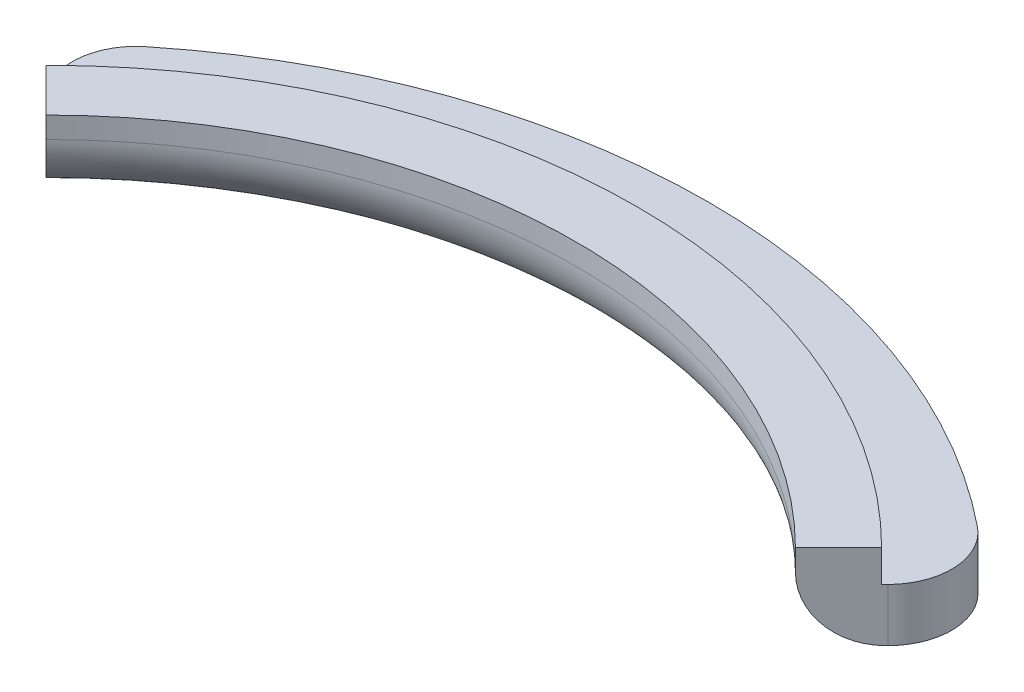
SolidWorks part; units mm, degrees
ref_plane "Front Plane" through (0, 0, 0) normal (0, 0, 1) x (1, 0, 0)
ref_plane "Top Plane" through (0, 0, 0) normal (0, 1, 0) x (1, 0, 0)
ref_plane "Right Plane" through (0, 0, 0) normal (1, 0, 0) x (0, 0, -1)
sketch "Sketch1" plane through (0, 0, 0) normal (0, 1, 0) x (1, 0, 0)
  line L0 (0, 0) -> (0, 15.875) construction
  line L1 (0, 0) -> (8.9803, 8.9803) construction
  line L2 (0, 0) -> (-8.9803, 8.9803) construction
  line L3 (-8.9803, 8.9803) -> (-11.2253, 11.2253)
  line L4 (8.9803, 8.9803) -> (11.2253, 11.2253)
  arc A0 (8.9803, 8.9803) -> (-8.9803, 8.9803) centre (0, 0) ccw
  arc A1 (11.2253, 11.2253) -> (-11.2253, 11.2253) centre (0, 0) ccw
  dimension "D1" = 31.75
  dimension "D2" = 25.4
  dimension "D3" = 45
  dimension "D4" = 45
extrude "Boss-Extrude1" add sketch "Sketch1" along normal blind 2.032
sketch "Sketch2" plane through (0, 2.032, 0) normal (0, 1, 0) x (1, 0, 0)
  line L0 (-11.2253, 11.2253) -> (-8.9803, 8.9803) construction
  line L1 (8.9803, 8.9803) -> (11.2253, 11.2253) construction
  line L2 (10.013, 10.013) -> (11.2253, 11.2253)
  line L3 (-11.2253, 11.2253) -> (-10.013, 10.013)
  arc A0 (-10.013, 10.013) -> (10.013, 10.013) centre (0, 0) cw
  arc A1 (11.2253, 11.2253) -> (-11.2253, 11.2253) centre (0, 0) ccw construction
  arc A2 (11.2253, 11.2253) -> (-11.2253, 11.2253) centre (0, 0) ccw
  point P3 (0, 0)
  dimension "D1" = 14.1605
extrude "Cut-Extrude1" cut sketch "Sketch2" against normal blind 0.762
fillet "Fillet2" radius 1.524 1 edges at (0, 0, -12.7)
fillet "Fillet1" radius 1.524 2 edges at (11.2253, 0.635, -11.2253) (-11.2253, 0.635, -11.2253)
